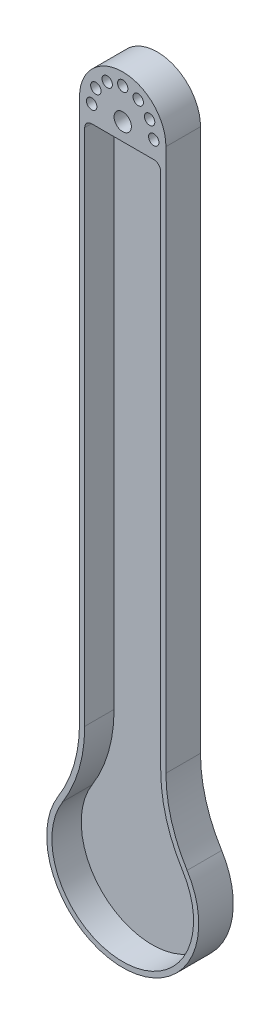
SolidWorks part; units mm, degrees
ref_plane "Front Plane" through (0, 0, 0) normal (0, 0, 1) x (1, 0, 0)
ref_plane "Top Plane" through (0, 0, 0) normal (0, 1, 0) x (1, 0, 0)
ref_plane "Right Plane" through (0, 0, 0) normal (1, 0, 0) x (0, 0, -1)
sketch "Sketch1" plane through (0, 0, 0) normal (0, 0, 1) x (1, 0, 0)
  line L0 (0, 0) -> (0, 241.3) construction
  line L1 (-15.875, 241.3) -> (-15.875, 41.8859)
  line L2 (15.875, 241.3) -> (15.875, 41.8859)
  arc A0 (15.875, 241.3) -> (-15.875, 241.3) centre (0, 241.3) ccw
  arc A1 (-23.6589, 14.8628) -> (23.6589, 14.8628) centre (0, 0) ccw
  arc A2 (23.6589, 14.8628) -> (15.875, 41.8859) centre (66.675, 41.8859) cw
  arc A3 (-15.875, 41.8859) -> (-23.6589, 14.8628) centre (-66.675, 41.8859) cw
  dimension "D2" = 50.8
  dimension "D1" = 241.3
  dimension "D3" = 31.75
extrude "Boss-Extrude1" add sketch "Sketch1" along normal blind 12.7
sketch "Sketch2" plane through (0, 0, 12.7) normal (0, 0, 1) x (1, 0, 0)
  line L0 (-11.43, 234.95) -> (11.43, 234.95)
  line L1 (0, 241.3) -> (0, -17.5772) construction
  line L2 (-13.97, 232.41) -> (-13.97, 41.8859)
  line L3 (13.97, 232.41) -> (13.97, 41.8859)
  arc A0 (-22.0458, 13.8494) -> (22.0458, 13.8494) centre (0, 0) ccw
  arc A1 (-11.43, 234.95) -> (-13.97, 232.41) centre (-11.43, 232.41) ccw
  arc A2 (13.97, 232.41) -> (11.43, 234.95) centre (11.43, 232.41) ccw
  arc A10 (-22.0458, 13.8494) -> (-13.97, 41.8859) centre (-66.675, 41.8859) ccw
  arc A11 (-22.0458, 13.8494) -> (-13.97, 41.8859) centre (-66.675, 41.8859) ccw
  arc A13 (13.97, 41.8859) -> (22.0458, 13.8494) centre (66.675, 41.8859) ccw
  arc A14 (13.97, 41.8859) -> (22.0458, 13.8494) centre (66.675, 41.8859) ccw
  point P9 (-61.0473, 59.1497)
  point P12 (-13.97, 234.95)
  point P15 (13.97, 234.95)
  dimension "D1" = 6.35
  dimension "D4" = 2.54
  dimension "D5" = 2.54
  dimension "D2" = 27.94
  dimension "D3" = 13.97
  dimension "D6" = 1.905
  dimension "D7" = 1.905
extrude "Cut-Extrude1" cut sketch "Sketch2" against normal blind 10.795
sketch "Sketch3" plane through (0, 0, 12.7) normal (0, 0, 1) x (1, 0, 0)
  circle A0 centre (0, 241.3) radius 3.175
extrude "Cut-Extrude2" cut sketch "Sketch3" against normal blind 23.622
sketch "Sketch4" plane through (0, 0, 12.7) normal (0, 0, 1) x (1, 0, 0)
  line L0 (0, 241.3) -> (-23.3538, 241.3) construction
  circle A0 centre (0, 241.3) radius 11.43 construction
  circle A1 centre (-11.4056, 241.3) radius 1.905
  circle A2 centre (-9.8775, 247.0028) radius 1.905
  circle A3 centre (-5.7028, 251.1775) radius 1.905
  circle A4 centre (0, 252.7056) radius 1.905
  circle A5 centre (5.7028, 251.1775) radius 1.905
  circle A6 centre (9.8775, 247.0028) radius 1.905
  circle A7 centre (11.4056, 241.3) radius 1.905
  point P20 (0, 241.3)
  dimension "D1" = 7
extrude "Cut-Extrude3" cut sketch "Sketch4" against normal blind 7.62
sketch "Sketch5" plane through (0, 0, 0) normal (0, 0, -1) x (-1, 0, 0)
  circle A0 centre (0, 241.3) radius 4.445
extrude "Cut-Extrude4" cut sketch "Sketch5" against normal blind 1.27
